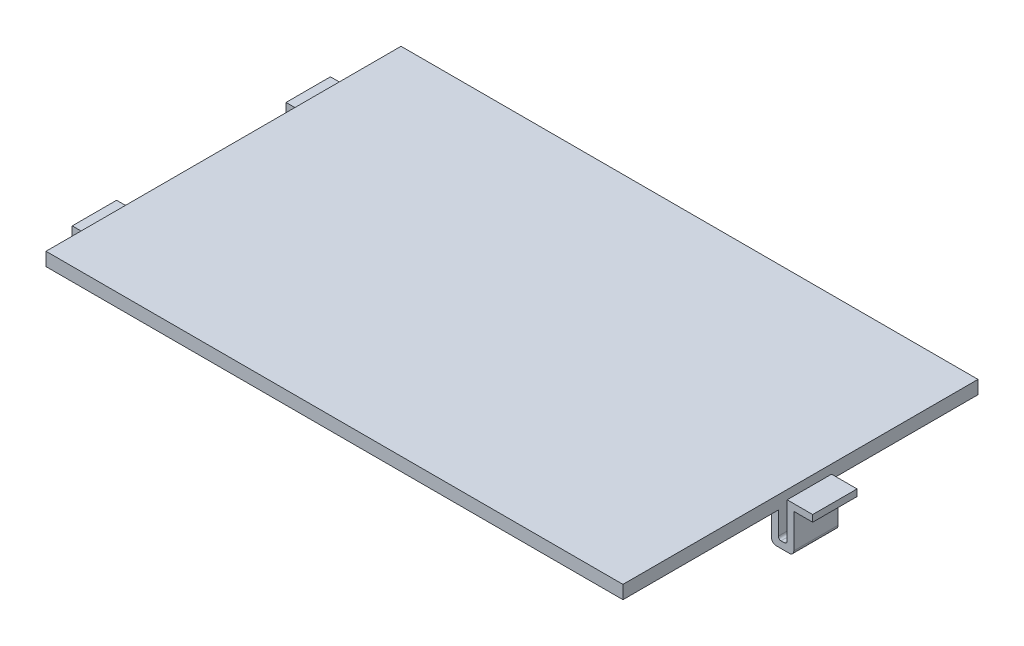
SolidWorks part; units mm, degrees
ref_plane "Front Plane" through (0, 0, 0) normal (0, 0, 1) x (1, 0, 0)
ref_plane "Top Plane" through (0, 0, 0) normal (0, 1, 0) x (1, 0, 0)
ref_plane "Right Plane" through (0, 0, 0) normal (1, 0, 0) x (0, 0, -1)
sketch "Sketch1" plane through (0, 0, 0) normal (0, 1, 0) x (1, 0, 0)
  line L1 (-65, 40) -> (65, 40)
  line L2 (-65, 40) -> (-65, -40)
  line L3 (-65, -40) -> (65, -40)
  line L4 (65, 40) -> (65, -40)
  line L5 (-65, 40) -> (65, -40) construction
  line L6 (-65, -40) -> (65, 40) construction
  point P0 (0, 0)
  dimension "D1" = 130
  dimension "D2" = 80
extrude "Boss-Extrude1" add sketch "Sketch1" along normal blind 3
sketch "Sketch2" plane through (0, 0, 0) normal (0, 0, 1) x (1, 0, 0)
  line L0 (63.5, 1.5) -> (63.5, -6.2055)
  line L1 (64.5, -7.2055) -> (67.5, -7.2055)
  line L2 (68.5, -6.2055) -> (68.5, 1.5)
  line L3 (68.5, 1.5) -> (72.7473, 1.5)
  line L5 (67, 3) -> (67, -5.1055)
  line L6 (66.4, -5.7055) -> (65.6, -5.7055)
  line L7 (65, -5.1055) -> (65, 1.5)
  line L8 (65, 3) -> (65, 0) construction
  line L9 (65, 1.5) -> (63.5, 1.5)
  line L11 (67, 3) -> (72.7473, 3)
  line L12 (72.7473, 3) -> (72.7473, 1.5)
  arc A0 (67.5, -7.2055) -> (68.5, -6.2055) centre (67.5, -6.2055) ccw
  arc A1 (63.5, -6.2055) -> (64.5, -7.2055) centre (64.5, -6.2055) ccw
  arc A2 (67, -5.1055) -> (66.4, -5.7055) centre (66.4, -5.1055) cw
  arc A3 (65.6, -5.7055) -> (65, -5.1055) centre (65.6, -5.1055) cw
  point P14 (68.5, -7.2055)
  point P17 (63.5, -7.2055)
  dimension "D2" = 1
  dimension "D4" = 1
  dimension "D5" = 0.6
  dimension "D1" = 5
  dimension "D3" = 1.5
extrude "Boss-Extrude2" add sketch "Sketch2" along normal blind 5 and the other way blind 5
sketch "Sketch3" plane through (0, 0, 0) normal (0, -1, 0) x (1, 0, 0)
  line L0 (-65, -40) -> (-65, 40) construction
  line L1 (-65, 29.0899) -> (-61, 29.0899)
  line L2 (-65, 29.0899) -> (-65, 19.0899)
  line L3 (-65, 19.0899) -> (-61, 19.0899)
  line L4 (-61, 29.0899) -> (-61, 19.0899)
  line L5 (5.613, 0) -> (-5.613, 0) construction
  line L6 (-65, -19.0899) -> (-61, -19.0899)
  line L7 (-61, -29.0899) -> (-61, -19.0899)
  line L8 (-65, -29.0899) -> (-61, -29.0899)
  line L9 (-65, -29.0899) -> (-65, -19.0899)
  dimension "D1" = 10
  dimension "D2" = 4
extrude "Boss-Extrude3" add sketch "Sketch3" along normal blind 2
sketch "Sketch4" plane through (-65, 0, 0) normal (-1, 0, 0) x (0, 0, 1)
  line L1 (-29.0899, -2) -> (-19.0899, -2)
  line L2 (-29.0899, -2) -> (-29.0899, 0)
  line L3 (-29.0899, 0) -> (-19.0899, 0)
  line L4 (-19.0899, -2) -> (-19.0899, 0)
  line L5 (19.0899, -2) -> (29.0899, -2)
  line L6 (19.0899, -2) -> (19.0899, 0)
  line L7 (19.0899, 0) -> (29.0899, 0)
  line L8 (29.0899, -2) -> (29.0899, 0)
extrude "Boss-Extrude4" add sketch "Sketch4" along normal blind 5
